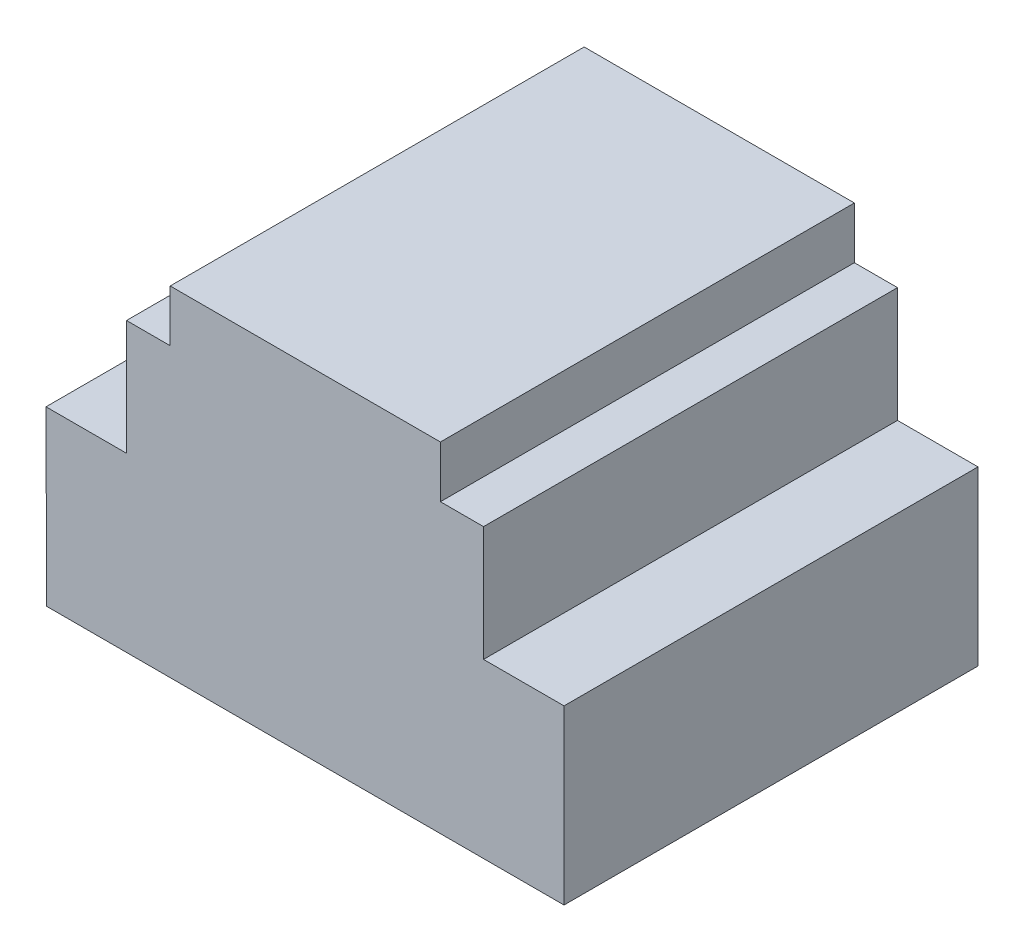
SolidWorks part; units mm, degrees
ref_plane "前视基准面" through (0, 0, 0) normal (0, 0, 1) x (1, 0, 0)
ref_plane "上视基准面" through (0, 0, 0) normal (0, 1, 0) x (1, 0, 0)
ref_plane "右视基准面" through (0, 0, 0) normal (1, 0, 0) x (0, 0, -1)
other "Configuration Table"
sketch "草图1" plane through (0, 0, 0) normal (0, 0, 1) x (1, 0, 0)
  line L0 (0, 0) -> (90, 0)
  line L1 (90, 0) -> (90, 30)
  line L2 (90, 30) -> (76, 30)
  line L3 (76, 30) -> (76, 50)
  line L4 (76, 50) -> (68.5, 50)
  line L5 (68.5, 50) -> (68.5, 59)
  line L6 (68.5, 59) -> (21.5, 59)
  line L7 (21.5, 59) -> (21.5, 50)
  line L8 (21.5, 50) -> (13.9, 50)
  line L9 (13.9, 50) -> (13.9, 30)
  line L10 (13.9, 30) -> (-0.1, 30)
  line L11 (-0.1, 30) -> (0, 0)
extrude "凸台-拉伸1" add sketch "草图1" along normal blind 72
